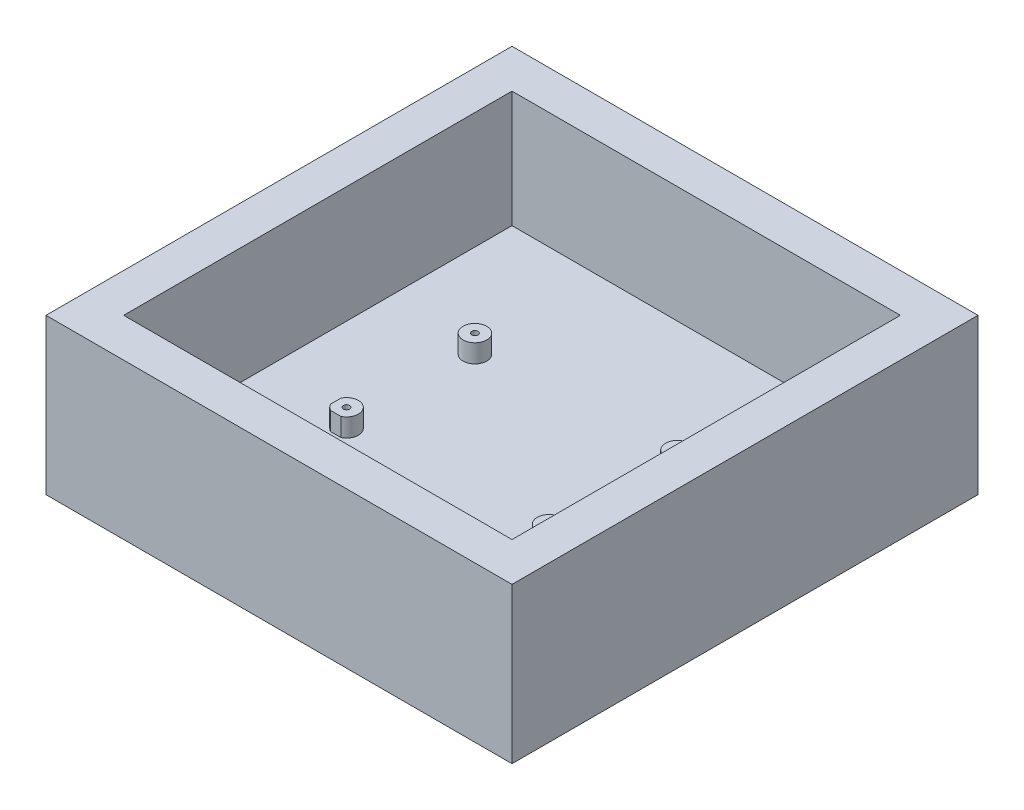
SolidWorks part; units mm, degrees
ref_plane "Front Plane" through (0, 0, 0) normal (0, 0, 1) x (1, 0, 0)
ref_plane "Top Plane" through (0, 0, 0) normal (0, 1, 0) x (1, 0, 0)
ref_plane "Right Plane" through (0, 0, 0) normal (1, 0, 0) x (0, 0, -1)
sketch "Sketch1" plane through (0, 0, 0) normal (0, 0, 1) x (1, 0, 0)
  line L1 (-11.0772, 255.1547) -> (141.3228, 255.1547)
  line L2 (-11.0772, 255.1547) -> (-11.0772, 204.3547)
  line L3 (-11.0772, 204.3547) -> (141.3228, 204.3547)
  line L4 (141.3228, 255.1547) -> (141.3228, 204.3547)
  line L5 (65.1228, 204.3547) -> (65.1228, 255.1547) construction
  line L6 (-11.0772, 229.7547) -> (141.3228, 229.7547) construction
  point P196 (65.1228, 229.7547)
  dimension "D1" = 152.4
  dimension "D2" = 50.8
extrude "Boss-Extrude2" add sketch "Sketch1" along normal blind 152.4
shell "Shell1" thickness 12.7
sketch "Sketch2" plane through (0, 217.0547, 0) normal (0, 1, 0) x (1, 0, 0)
  line L0 (65.1228, -12.7) -> (65.1228, -139.7) construction
  line L1 (28.5028, -51.7) -> (101.7428, -51.7)
  line L2 (28.5028, -51.7) -> (28.5028, -100.7)
  line L3 (28.5028, -100.7) -> (101.7428, -100.7)
  line L4 (101.7428, -51.7) -> (101.7428, -100.7)
  line L5 (65.1228, -100.7) -> (65.1228, -51.7) construction
  line L6 (28.5028, -76.2) -> (101.7428, -76.2) construction
  line L7 (128.6228, -12.7) -> (1.6228, -12.7) construction
  line L8 (128.6228, -139.7) -> (1.6228, -139.7) construction
  line L9 (1.6228, -76.2) -> (128.6228, -76.2) construction
  line L10 (1.6228, -139.7) -> (1.6228, -12.7) construction
  line L11 (128.6228, -139.7) -> (128.6228, -12.7) construction
  line L12 (32.0028, -51.7) -> (32.0028, -55.2) construction
  line L19 (32.0028, -55.2) -> (28.5028, -55.2) construction
  line L20 (98.2428, -55.2) -> (98.2428, -51.7) construction
  line L21 (98.2428, -51.7) -> (98.2428, -55.2) construction
  line L22 (98.2428, -55.2) -> (101.7428, -55.2) construction
  line L23 (98.2428, -100.7) -> (98.2428, -97.2) construction
  line L24 (98.2428, -97.2) -> (101.7428, -97.2) construction
  line L25 (32.0028, -97.2) -> (32.0028, -100.7) construction
  line L26 (32.0028, -100.7) -> (32.0028, -97.2) construction
  line L27 (32.0028, -97.2) -> (28.5028, -97.2) construction
  circle A1 centre (32.0028, -55.2) radius 3.8778
  circle A2 centre (98.2428, -55.2) radius 3.8778
  circle A3 centre (98.2428, -97.2) radius 3.8778
  circle A4 centre (32.0028, -97.2) radius 3.8778
  point P17 (65.1228, -76.2)
  point P140 (65.1228, -76.2)
  dimension "D5" = 3.5
  dimension "D1" = 73.24
  dimension "D2" = 49
  dimension "D3" = 3.5
  dimension "D4" = 3.5
  dimension "D6" = 3.5
  dimension "D7" = 3.5
  dimension "D8" = 3.5
  dimension "D9" = 3.5
  dimension "D10" = 3.5
extrude "Boss-Extrude3" add sketch "Sketch2" along normal blind 6 contours L3 A4 L2 | L3 A3 L4 | L4 A2 L1 | A1
hole_wizard "M2.5x0.45 Tapped Hole3" positions "Sketch8" profile "Sketch9" tap size "M2.5x0.45" standard "ANSI Metric"
sketch "Sketch8" plane through (0, 223.0547, 0) normal (0, 1, 0) x (1, 0, 0)
  point P0 (32.0028, -55.2)
  point P3 (98.2428, -55.2)
  point P6 (98.2428, -97.2)
  point P9 (32.0028, -97.2)
cosmetic thread "Hole Thread12" parameters "D1"=5.08, "D2"=2.5
cosmetic thread "Hole Thread13" parameters "D1"=5.08, "D2"=2.5
cosmetic thread "Hole Thread14" parameters "D1"=5.08, "D2"=2.5
cosmetic thread "Hole Thread15" parameters "D1"=5.08, "D2"=2.5
sketch "Sketch9" plane through (32.0028, 223.0547, 55.2) normal (1, 0, 0) x (0, 0, 1)
  line L0 (0, 0) -> (0, 5.6159)
  line L1 (0, 5.6159) -> (1.025, 5)
  line L2 (1.025, 5) -> (1.025, 0)
  line L5 (1.025, 0) -> (0, 0)
  line L10 (0, 5.6159) -> (-1.025, 5) construction
  line L11 (0, -6.35) -> (0, 107.95) construction
  dimension "Tap Drill Dia." = 2.05
  dimension "Tap Drill Depth" = 5
  dimension "Drill Angle" = 118
sketch "Sketch10" plane through (0, 204.3547, 0) normal (0, -1, 0) x (-1, 0, 0)
  line L0 (-65.1228, 0) -> (-65.1228, -152.4) construction
  line L1 (11.0772, 0) -> (-141.3228, 0) construction
  line L2 (11.0772, -152.4) -> (-141.3228, -152.4) construction
  line L3 (-65.1228, -152.4) -> (-65.1228, -76.2) construction
  line L4 (-65.1228, -76.2) -> (-141.3228, -76.2) construction
  line L5 (-141.3228, -152.4) -> (-141.3228, 0) construction
  line L6 (-141.3228, -76.2) -> (11.0772, -76.2) construction
  line L7 (11.0772, -152.4) -> (11.0772, 0) construction
